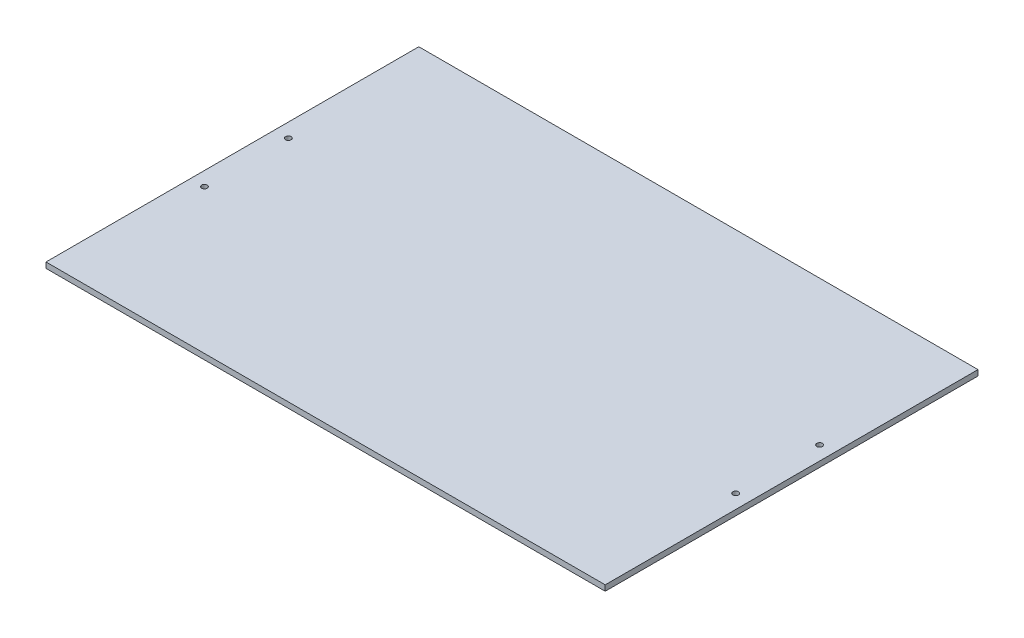
SolidWorks part; units mm, degrees
material "Balsa"
ref_plane "Plano frontal" through (0, 0, 0) normal (0, 0, 1) x (1, 0, 0)
ref_plane "Plano superior" through (0, 0, 0) normal (0, 1, 0) x (1, 0, 0)
ref_plane "Plano direito" through (0, 0, 0) normal (1, 0, 0) x (0, 0, -1)
sketch "Esboço1" plane through (0, 0, 0) normal (0, 1, 0) x (1, 0, 0)
  line L0 (-142.5, -22.5) -> (-142.5, 22.5) construction
  line L1 (-150, -100) -> (150, -100)
  line L2 (-150, -100) -> (-150, 100)
  line L3 (-150, 100) -> (150, 100)
  line L4 (150, -100) -> (150, 100)
  line L5 (-150, -100) -> (150, 100) construction
  line L6 (-150, 100) -> (150, -100) construction
  line L7 (0, 100) -> (0, -100) construction
  line L8 (142.5, -22.5) -> (142.5, 22.5) construction
  circle A0 centre (-142.5, 22.5) radius 1.5
  circle A1 centre (-142.5, -22.5) radius 1.5
  circle A2 centre (142.5, -22.5) radius 1.5
  circle A3 centre (142.5, 22.5) radius 1.5
  point P0 (0, 0)
  point P20 (-142.5, 0)
  dimension "D4" = 3
  dimension "D1" = 200
  dimension "D2" = 300
  dimension "D3" = 45
  dimension "D5" = 7.5
  dimension "D6" = 100
extrude "Ressalto-extrusão1" add sketch "Esboço1" along normal blind 3
